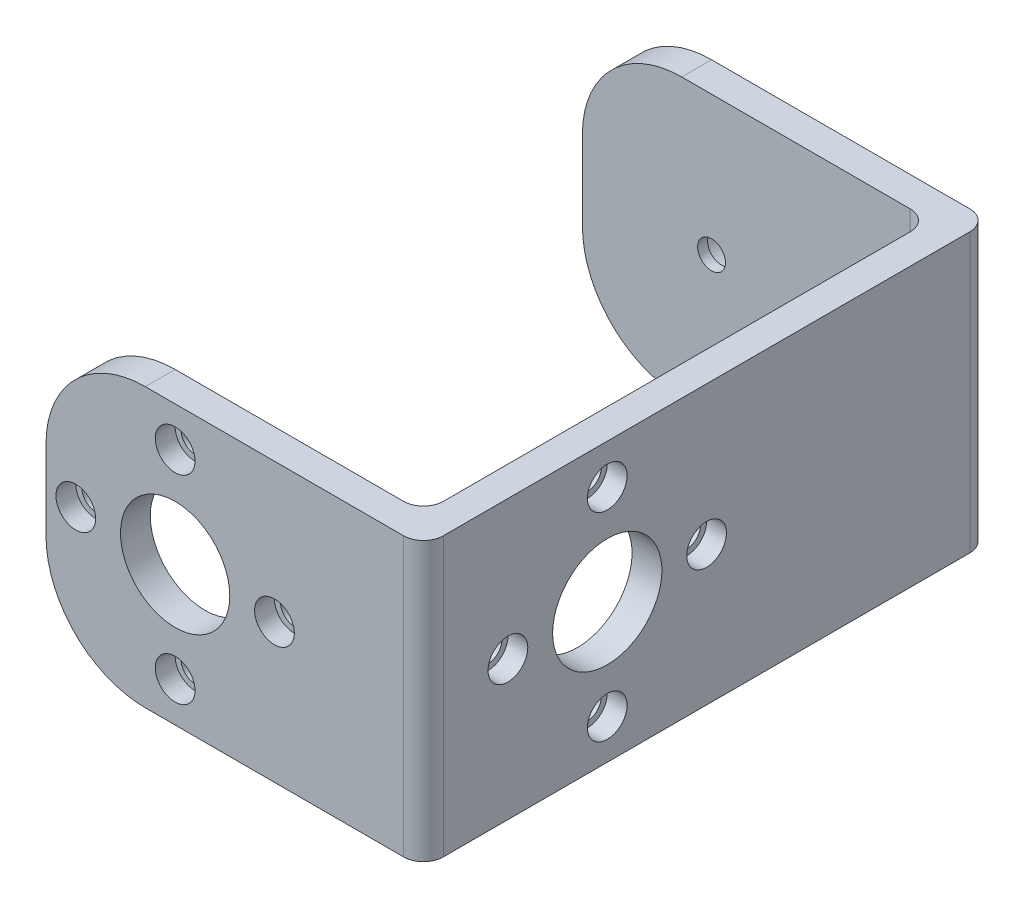
SolidWorks part; units mm, degrees
material "Esun Hard Tough Resin"
ref_plane "Front Plane" through (0, 0, 0) normal (0, 0, 1) x (1, 0, 0)
ref_plane "Top Plane" through (0, 0, 0) normal (0, 1, 0) x (1, 0, 0)
ref_plane "Right Plane" through (0, 0, 0) normal (1, 0, 0) x (0, 0, -1)
sketch "Sketch1" plane through (0, 0, 0) normal (0, 1, 0) x (1, 0, 0)
  line L1 (19, -28.5) -> (-19, -28.5)
  line L2 (19, -28.5) -> (19, 28.5)
  line L3 (19, 28.5) -> (-19, 28.5)
  line L4 (-19, -28.5) -> (-19, 28.5)
  line L5 (19, -28.5) -> (-19, 28.5) construction
  line L6 (19, 28.5) -> (-19, -28.5) construction
  line L7 (-19, 25.5) -> (16, 25.5)
  line L8 (-19, 25.5) -> (-19, -25.5)
  line L9 (-19, -25.5) -> (16, -25.5)
  line L10 (16, 25.5) -> (16, -25.5)
  point P0 (0, 0)
  point P10 (16, 0)
  dimension "D1" = 51
  dimension "D2" = 3
  dimension "D3" = 35
  dimension "D4" = 3
extrude "Boss-Extrude1" add sketch "Sketch1" along normal blind 28 contours L7 L10 L9 L4 L1 L2 L3
sketch "Sketch2" plane through (16, 0, 0) normal (-1, 0, 0) x (0, 0, 1)
  line L0 (0, 0) -> (0, 28) construction
  line L1 (-25.5, 0) -> (25.5, 0) construction
  line L2 (-25.5, 28) -> (25.5, 28) construction
  line L3 (0, 28) -> (0, 14) construction
  line L4 (0, 14) -> (25.5, 14) construction
  line L6 (2.9289, 21.0711) -> (17.0711, 6.9289) construction
  line L7 (25.5, 28) -> (25.5, 0) construction
  line L8 (17.0711, 21.0711) -> (2.9289, 6.9289) construction
  circle A0 centre (10, 14) radius 10 construction
  circle A1 centre (10, 4) radius 1.4
  circle A2 centre (10, 24) radius 1.4
  circle A4 centre (0, 14) radius 1.4
  circle A5 centre (20, 14) radius 1.4
  circle A8 centre (10, 14) radius 5.5
  dimension "D4" = 2.8
  dimension "D5" = 11
  dimension "D2" = 10
  dimension "D3" = 45
  dimension "D6" = 45
extrude "Cut-Extrude1" cut sketch "Sketch2" against normal through all
sketch "Sketch3" plane through (0, 0, 28.5) normal (0, 0, 1) x (1, 0, 0)
  line L0 (-19, 28) -> (-19, 0) construction
  line L1 (-16, 14) -> (4, 14) construction
  line L3 (-6, 4) -> (-6, 24) construction
  circle A0 centre (-6, 14) radius 10 construction
  circle A1 centre (-16, 14) radius 1.4
  circle A3 centre (-6, 4) radius 1.4
  circle A5 centre (4, 14) radius 1.4
  circle A7 centre (-6, 24) radius 1.4
  circle A9 centre (-6, 14) radius 5.5
  point P5 (-19, 14)
  dimension "D2" = 20
  dimension "D5" = 11
  dimension "D3" = 2.8
  dimension "D1" = 6
extrude "Cut-Extrude2" cut sketch "Sketch3" against normal up to next
sketch "Sketch4" plane through (0, 0, -28.5) normal (0, 0, -1) x (-1, 0, 0)
  line L0 (16, 14) -> (-4, 14) construction
  circle A0 centre (6, 14) radius 1.4
  dimension "D1" = 2.8
extrude "Cut-Extrude3" cut sketch "Sketch4" against normal up to next
sketch "Sketch5" plane through (0, 0, 28.5) normal (0, 0, 1) x (1, 0, 0)
  circle A0 centre (-16, 14) radius 2
  circle A2 centre (-6, 24) radius 2
  circle A4 centre (4, 14) radius 2
  circle A6 centre (-6, 4) radius 2
  circle A9 centre (-6, 4) radius 1.4 construction
  circle A11 centre (4, 14) radius 1.4 construction
  circle A13 centre (-6, 24) radius 1.4 construction
  dimension "D1" = 4
extrude "Cut-Extrude4" cut sketch "Sketch5" against normal blind 2
sketch "Sketch6" plane through (19, 0, 0) normal (1, 0, 0) x (0, 0, -1)
  circle A1 centre (-10, 24) radius 2
  circle A4 centre (0, 14) radius 2
  circle A6 centre (-10, 4) radius 2
  circle A8 centre (-20, 14) radius 2
  circle A12 centre (-10, 24) radius 1.4 construction
  circle A14 centre (0, 14) radius 1.4 construction
  circle A16 centre (-10, 4) radius 1.4 construction
  circle A18 centre (-20, 14) radius 1.4 construction
  dimension "D1" = 4
extrude "Cut-Extrude5" cut sketch "Sketch6" against normal blind 2
sketch "Sketch7" plane through (0, 0, -28.5) normal (0, 0, -1) x (-1, 0, 0)
  circle A0 centre (6, 14) radius 2.5
  dimension "D1" = 5
extrude "Cut-Extrude6" cut sketch "Sketch7" against normal blind 2
fillet "Fillet1" radius 10 4 edges at (-19, 0, 27) (-19, 28, 27) (-19, 0, -27) (-19, 28, -27)
fillet "Fillet2" radius 2 4 edges at (19, 14, -28.5) (19, 14, 28.5) (16, 14, 25.5) (16, 14, -25.5)
